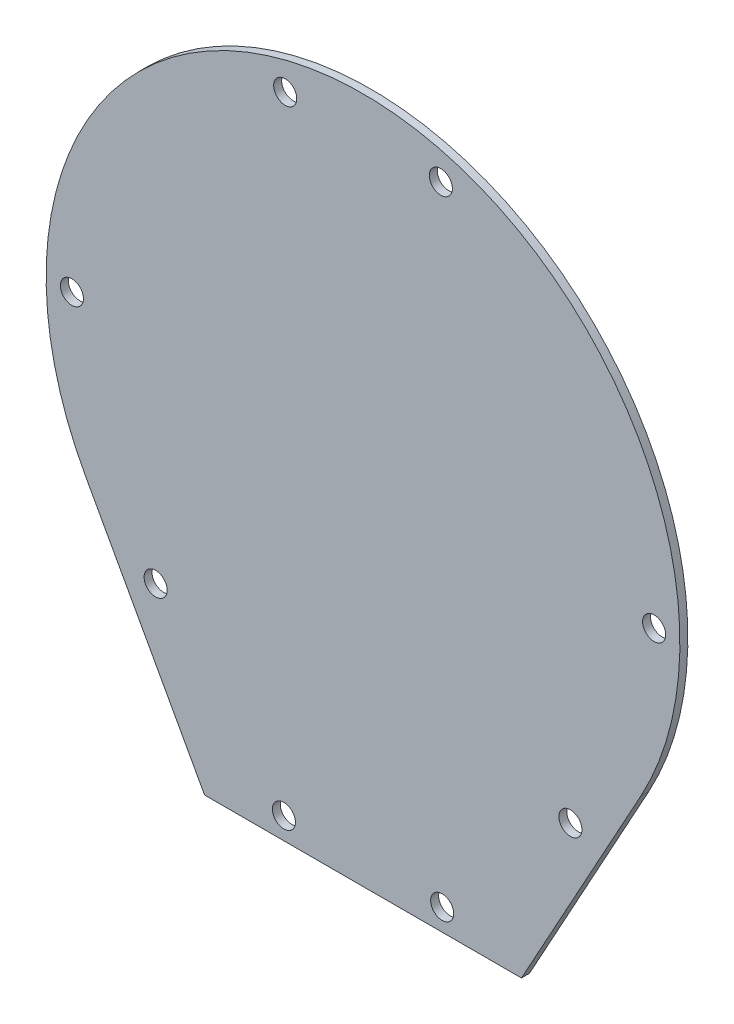
SolidWorks part; units mm, degrees
ref_plane "Plano frontal" through (0, 0, 0) normal (0, 0, 1) x (1, 0, 0)
ref_plane "Plano superior" through (0, 0, 0) normal (0, 1, 0) x (1, 0, 0)
ref_plane "Plano direito" through (0, 0, 0) normal (1, 0, 0) x (0, 0, -1)
sketch "Sketch1" plane through (0, 0, 0) normal (0, 0, 1) x (1, 0, 0)
  line L0 (-15, -35) -> (-7.5, -35)
  line L1 (-15, -35) -> (15, -35)
  line L4 (-15, -35) -> (-7.5, -35)
  line L7 (15, -35) -> (26.2929, -14.4459)
  line L16 (-15, -35) -> (-26.2929, -14.4459)
  arc A2 (26.2929, -14.4459) -> (-26.2929, -14.4459) centre (0, 0) ccw
  point P10 (0, -35)
  dimension "D3" = 60
  dimension "D5" = 30
  dimension "D6" = 7.5
extrude "Boss-Extrude1" add sketch "Sketch1" along normal blind 0.7544
sketch "Esboço1" plane through (0, 0, 0.7544) normal (0, 0, 1) x (1, 0, 0)
  line L0 (-15, -35) -> (-7.4931, -35)
  line L1 (-15, -35) -> (15, -35) construction
  line L2 (-7.4931, -35) -> (-7.4931, -32.938)
  line L3 (-15, -35) -> (-15, -19.984)
  line L4 (-15, -19.984) -> (-19.634, -19.984)
  line L5 (-19.634, -19.984) -> (-19.634, -0.045)
  line L6 (-19.634, -0.045) -> (-27.559, -0.045)
  line L7 (-27.559, -0.045) -> (-27.559, 26.447)
  line L8 (-27.559, 26.447) -> (-7.366, 26.447)
  line L9 (0, 30) -> (0, -35)
  line L10 (27.559, 26.447) -> (7.366, 26.447)
  line L11 (27.559, -0.045) -> (27.559, 26.447)
  line L12 (19.634, -0.045) -> (27.559, -0.045)
  line L13 (19.634, -19.984) -> (19.634, -0.045)
  line L14 (15, -19.984) -> (19.634, -19.984)
  line L15 (15, -35) -> (15, -19.984)
  line L16 (7.4931, -35) -> (7.4931, -32.938)
  line L17 (15, -35) -> (7.4931, -35)
  circle A0 centre (-7.4931, -32.938) radius 1.092
  circle A1 centre (-19.634, -19.984) radius 1.092
  circle A2 centre (-27.559, -0.045) radius 1.092
  circle A3 centre (-7.366, 26.447) radius 1.092
  arc A4 (26.2929, -14.4459) -> (-26.2929, -14.4459) centre (0, 0) ccw construction
  circle A5 centre (7.366, 26.447) radius 1.092
  circle A6 centre (27.559, -0.045) radius 1.092
  circle A7 centre (19.634, -19.984) radius 1.092
  circle A8 centre (7.4931, -32.938) radius 1.092
  dimension "D3" = 2.184
  dimension "D6" = 2.184
  dimension "D9" = 2.184
  dimension "D12" = 2.184
  dimension "D1" = 7.5069
  dimension "D2" = 2.062
  dimension "D4" = 15.016
  dimension "D5" = 4.634
  dimension "D7" = 19.939
  dimension "D8" = 7.925
  dimension "D10" = 26.492
  dimension "D11" = 20.193
extrude "Corte-extrusão1" cut sketch "Esboço1" against normal blind 10
